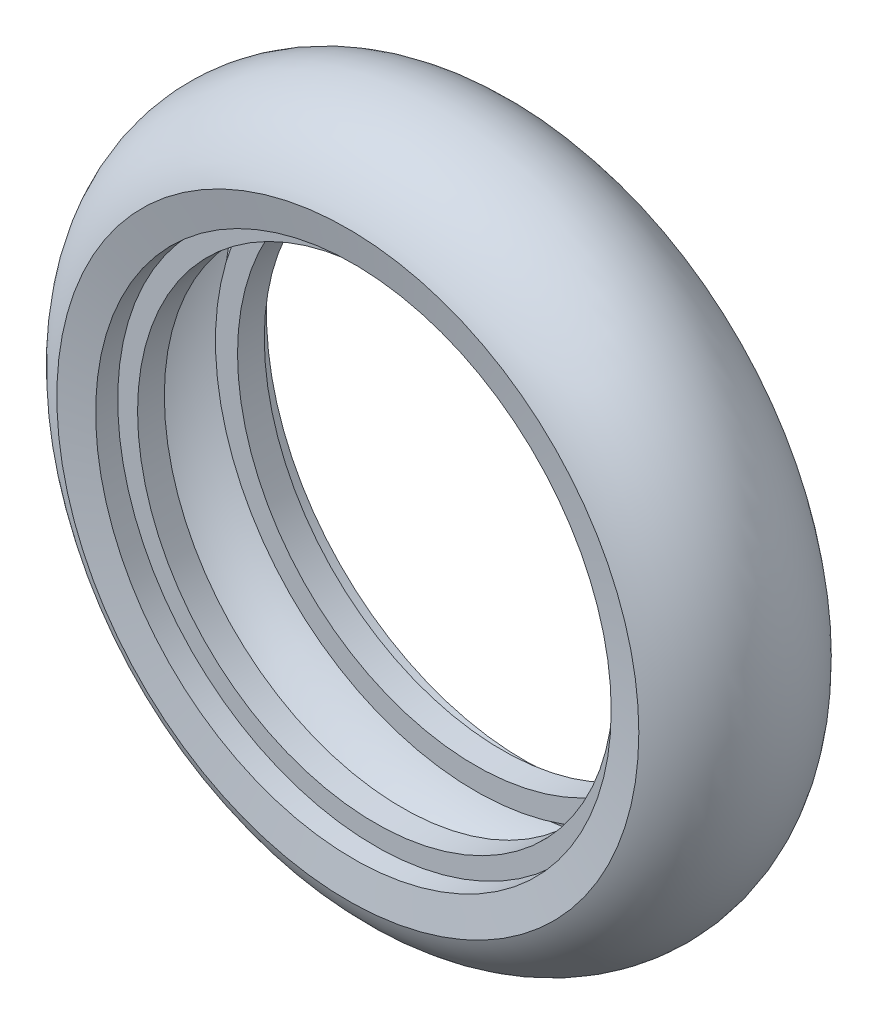
SolidWorks part; units mm, degrees
ref_plane "Piano frontale" through (0, 0, 0) normal (0, 0, 1) x (1, 0, 0)
ref_plane "Piano superiore" through (0, 0, 0) normal (0, 1, 0) x (1, 0, 0)
ref_plane "Piano destro" through (0, 0, 0) normal (1, 0, 0) x (0, 0, -1)
sketch "Schizzo1" plane through (0, 0, 0) normal (1, 0, 0) x (0, 0, -1)
  line L0 (-16.5, -6.875) -> (-15.485, -0.855)
  line L1 (0, -17.875) -> (0, 6.5173) construction
  line L2 (-15.485, -0.855) -> (-11.485, -0.855)
  line L3 (-11.485, -0.855) -> (-11.485, 2.745)
  line L4 (-11.485, 2.745) -> (-6.635, 2.745)
  line L5 (-6.635, 2.745) -> (-6.635, -1.255)
  line L6 (-13.3906, -6.4774) -> (-12.5268, -1.3538)
  line L8 (-6.635, -1.255) -> (-12.5268, -1.3538)
  line L9 (6.635, -1.255) -> (12.5268, -1.3538)
  line L10 (13.3906, -6.4774) -> (12.5268, -1.3538)
  line L11 (6.635, 2.745) -> (6.635, -1.255)
  line L12 (11.485, 2.745) -> (6.635, 2.745)
  line L13 (11.485, -0.855) -> (11.485, 2.745)
  line L14 (15.485, -0.855) -> (11.485, -0.855)
  line L15 (16.5, -6.875) -> (15.485, -0.855)
  line L16 (-83.137, 45.875) -> (60.7707, 45.875) construction
  arc A0 (-16.5, -6.875) -> (0, -17.875) centre (0, 0) ccw
  arc A1 (-13.3906, -6.4774) -> (0, -14.875) centre (0, 0) ccw
  arc A2 (13.3906, -6.4774) -> (0, -14.875) centre (0, 0) cw
  arc A3 (16.5, -6.875) -> (0, -17.875) centre (0, 0) cw
  dimension "D1" = 3
  dimension "D2" = 33
  dimension "D3" = 4
  dimension "D4" = 22.97
  dimension "D5" = 4.85
  dimension "D6" = 43.13
  dimension "D7" = 3.6
  dimension "D8" = 4
  dimension "D9" = 127.5
  dimension "D10" = 11
revolve "Rivoluzione1" add sketch "Schizzo1" angle 360 about L16
